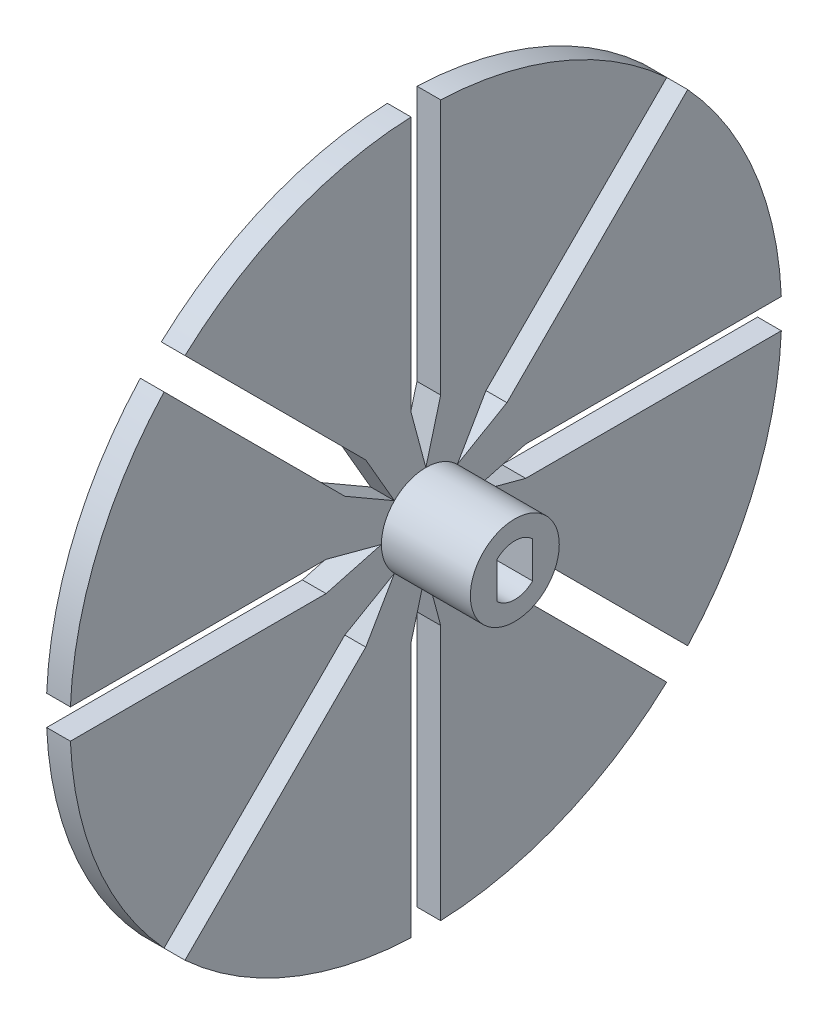
SolidWorks part; units mm, degrees
ref_plane "Front Plane" through (0, 0, 0) normal (0, 0, 1) x (1, 0, 0)
ref_plane "Top Plane" through (0, 0, 0) normal (0, 1, 0) x (1, 0, 0)
ref_plane "Right Plane" through (0, 0, 0) normal (1, 0, 0) x (0, 0, -1)
sketch "Sketch1" plane through (0, 0, 0) normal (1, 0, 0) x (0, 0, -1)
  line L0 (-1.905, -1.9562) -> (-1.905, 1.9562)
  line L1 (1.905, -1.9562) -> (1.905, 1.9562)
  arc A0 (-1.905, -1.9562) -> (1.905, -1.9562) centre (0, 0) ccw
  circle A1 centre (0, 0) radius 4.7625
  arc A2 (1.905, 1.9562) -> (-1.905, 1.9562) centre (0, 0) ccw
  dimension "D1" = 5.461
  dimension "D3" = 9.525
  dimension "D2" = 3.81
extrude "Boss-Extrude1" add sketch "Sketch1" along normal blind 9.525 contours A1
sketch "Sketch2" plane through (0, 0, 0) normal (-1, 0, 0) x (0, 0, 1)
  circle A0 centre (0, 0) radius 38.1
  dimension "D1" = 76.2
extrude "Boss-Extrude2" add sketch "Sketch2" along normal blind 2.54
sketch "Sketch3" plane through (0, 0, 0) normal (1, 0, 0) x (0, 0, -1)
  line L0 (-1.5875, 10.6871) -> (0, 4.7625)
  line L1 (-1.5875, 38.1) -> (1.5875, 38.1)
  line L2 (-1.5875, 38.1) -> (-1.5875, 10.6871)
  line L4 (1.5875, 38.1) -> (1.5875, 10.6871)
  line L5 (0, 4.7625) -> (1.5875, 10.6871)
  circle A0 centre (0, 0) radius 38.1 construction
  circle A2 centre (0, 0) radius 4.7625 construction
  circle A3 centre (0, 0) radius 4.7625 construction
  point P1 (0, 0)
  point P2 (0, 0)
  dimension "D1" = 3.175
  dimension "D2" = 15
extrude "Cut-Extrude1" cut sketch "Sketch3" against normal through all both and the other way through all contours L2 L0 L5 L4 L1
pattern_circular "CirPattern1" count 8 over 360 about axis through (0, 0, 0) along (1, 0, 0) of "Cut-Extrude1"
